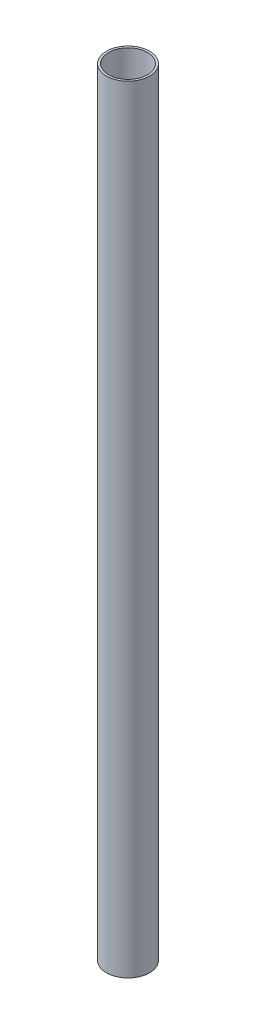
SolidWorks part; units mm, degrees
ref_plane "前视基准面" through (0, 0, 0) normal (0, 0, 1) x (1, 0, 0)
ref_plane "上视基准面" through (0, 0, 0) normal (0, 1, 0) x (1, 0, 0)
ref_plane "右视基准面" through (0, 0, 0) normal (1, 0, 0) x (0, 0, -1)
sketch "草图1" plane through (0, 0, 0) normal (0, 1, 0) x (1, 0, 0)
  circle A0 centre (0, 0) radius 10
  dimension "D1" = 20
extrude "1mm" add sketch "草图1" along normal mid plane 360 thin thin type one direction reverse wall 1
